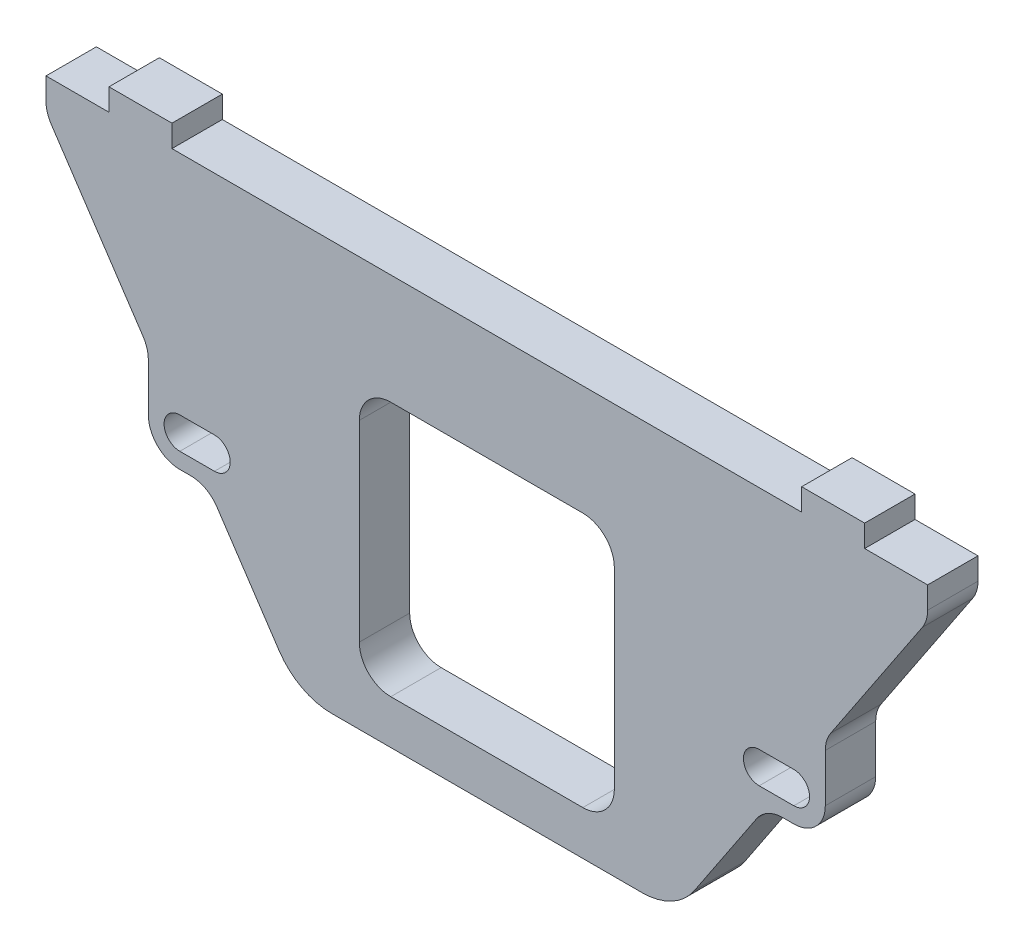
SolidWorks part; units mm, degrees
material "Q355"
ref_plane "前视基准面" through (0, 0, 0) normal (0, 0, 1) x (1, 0, 0)
ref_plane "上视基准面" through (0, 0, 0) normal (0, 1, 0) x (1, 0, 0)
ref_plane "右视基准面" through (0, 0, 0) normal (1, 0, 0) x (0, 0, -1)
sketch "草图1" plane through (0, 0, 0) normal (0, 0, 1) x (1, 0, 0)
  line L0 (0, 0) -> (0, 169.3404) construction
  line L1 (60, 0) -> (-60, 0)
  line L2 (-60, 0) -> (-88.6667, 43)
  line L3 (-88.6667, 43) -> (-107.5, 43)
  line L4 (-107.5, 43) -> (-107.5, 71.25)
  line L5 (-107.5, 71.25) -> (-140, 120)
  line L6 (-140, 120) -> (-140, 130)
  line L7 (-140, 130) -> (-120, 130)
  line L8 (-120, 130) -> (-120, 137)
  line L9 (-120, 137) -> (-100, 137)
  line L10 (-100, 137) -> (-100, 130)
  line L11 (-100, 130) -> (100, 130)
  line L12 (40.5, 14) -> (-40.5, 14)
  line L13 (-40.5, 14) -> (-40.5, 95)
  line L14 (-40.5, 95) -> (40.5, 95)
  line L15 (40.5, 14) -> (40.5, 95)
  line L16 (100, 137) -> (100, 130)
  line L17 (120, 137) -> (100, 137)
  line L18 (120, 130) -> (120, 137)
  line L19 (140, 130) -> (120, 130)
  line L20 (140, 120) -> (140, 130)
  line L21 (107.5, 71.25) -> (140, 120)
  line L22 (107.5, 43) -> (107.5, 71.25)
  line L23 (88.6667, 43) -> (107.5, 43)
  line L24 (60, 0) -> (88.6667, 43)
  point P17 (0, 95)
  point P20 (0, 14)
  point P21 (0, 130)
  dimension "D1" = 120
  dimension "D2" = 130
  dimension "D3" = 10
  dimension "D4" = 280
  dimension "D5" = 43
  dimension "D6" = 215
  dimension "D7" = 200
  dimension "D8" = 20
  dimension "D9" = 7
  dimension "D10" = 81
  dimension "D11" = 81
  dimension "D12" = 14
extrude "凸台-拉伸1" add sketch "草图1" along normal mid plane 16
fillet "圆角1" radius 10 6 edges at (40.5, 14, 0) (-40.5, 14, 0) (40.5, 95, 0) (-40.5, 95, 0) (107.5, 43, 0) (-107.5, 43, 0)
sketch "草图2" plane through (0, 0, 8) normal (0, 0, 1) x (1, 0, 0)
  line L0 (-97.5, 53) -> (-86.5, 53) construction
  line L1 (-97.5, 58) -> (-86.5, 58)
  line L2 (-97.5, 48) -> (-86.5, 48)
  line L3 (97.5, 53) -> (86.5, 53) construction
  line L4 (97.5, 48) -> (86.5, 48)
  line L5 (97.5, 58) -> (86.5, 58)
  arc A0 (-97.5, 58) -> (-97.5, 48) centre (-97.5, 53) ccw
  arc A1 (-86.5, 48) -> (-86.5, 58) centre (-86.5, 53) ccw
  arc A2 (97.5, 48) -> (97.5, 58) centre (97.5, 53) ccw
  arc A3 (86.5, 58) -> (86.5, 48) centre (86.5, 53) ccw
  point P3 (-92, 53)
  point P11 (92, 53)
  dimension "D1" = 5
  dimension "D2" = 11
extrude "切除-拉伸1" cut sketch "草图2" against normal blind 16
fillet "圆角2" radius 20 2 edges at (60, 0, 0) (-60, 0, 0)
fillet "圆角3" radius 10 6 edges at (140, 120, 0) (-140, 120, 0) (-107.5, 71.25, 0) (-88.6667, 43, 0) (107.5, 71.25, 0) (88.6667, 43, 0)
